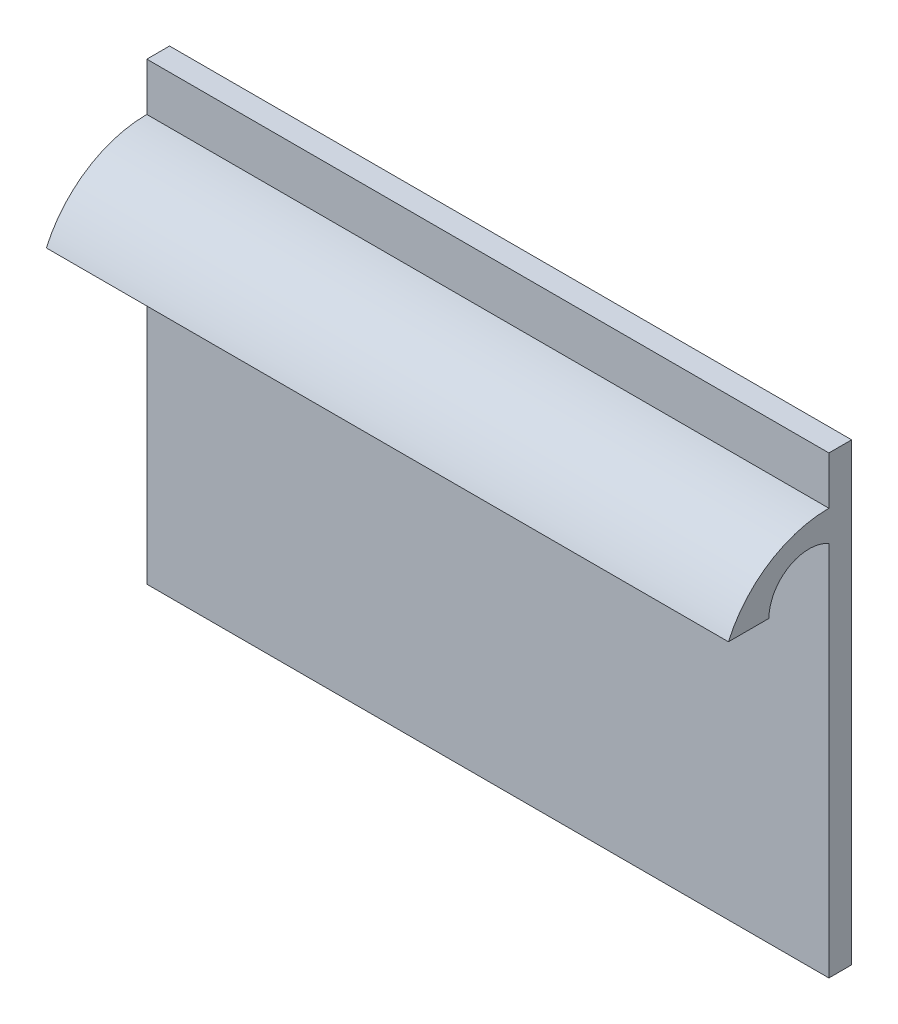
SolidWorks part; units mm, degrees
ref_plane "Front Plane" through (0, 0, 0) normal (0, 0, 1) x (1, 0, 0)
ref_plane "Top Plane" through (0, 0, 0) normal (0, 1, 0) x (1, 0, 0)
ref_plane "Right Plane" through (0, 0, 0) normal (1, 0, 0) x (0, 0, -1)
sketch "Sketch1" plane through (0, 0, 0) normal (0, 0, 1) x (1, 0, 0)
  line L1 (-150, 100) -> (150, 100)
  line L2 (-150, 100) -> (-150, -100)
  line L3 (-150, -100) -> (150, -100)
  line L4 (150, 100) -> (150, -100)
  line L5 (-150, 100) -> (150, -100) construction
  line L6 (-150, -100) -> (150, 100) construction
  point P0 (0, 0)
  dimension "D1" = 200
  dimension "D2" = 300
extrude "Boss-Extrude1" add sketch "Sketch1" along normal blind 10
sketch "Sketch4" plane through (150, 0, 0) normal (1, 0, 0) x (0, 0, -1)
  line L0 (-10, 78.9332) -> (-10, 65.5215)
  line L1 (-10, -100) -> (-10, 100) construction
  line L2 (-54.1761, 50.154) -> (-36.3617, 50.154)
  arc A0 (-10, 78.9332) -> (-54.1761, 50.154) centre (-10, 30.6384) ccw
  arc A1 (-36.3617, 50.154) -> (-10, 65.5215) centre (-18.7016, 50.154) cw
extrude "Boss-Extrude2" add sketch "Sketch4" against normal blind 300
